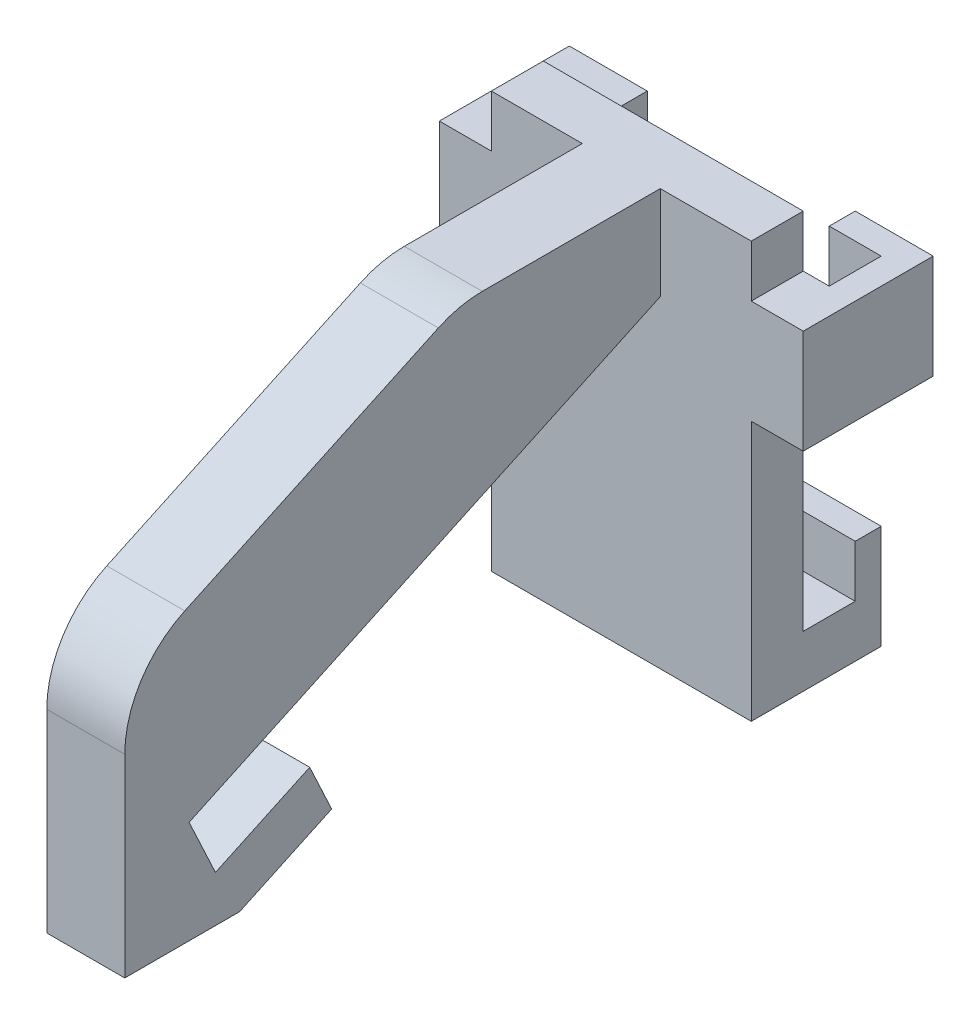
SolidWorks part; units mm, degrees
ref_plane "Front" through (0, 0, 0) normal (0, 0, 1) x (1, 0, 0)
ref_plane "Top" through (0, 0, 0) normal (0, 1, 0) x (1, 0, 0)
ref_plane "Right" through (0, 0, 0) normal (1, 0, 0) x (0, 0, -1)
sketch "Sketch2" plane through (0, 0, 0) normal (1, 0, 0) x (0, 0, -1)
  line L0 (0, 0) -> (25, 0)
  line L1 (25, 0) -> (25, 20)
  line L2 (25, 20) -> (20, 20)
  line L3 (20, 20) -> (20, 10)
  line L4 (20, 10) -> (10, 10)
  line L5 (10, 10) -> (10, 80)
  line L6 (10, 80) -> (0, 80)
  line L7 (0, 80) -> (0, 0)
  dimension "D1" = 25
  dimension "D2" = 10
  dimension "D3" = 5
  dimension "D4" = 80
  dimension "D5" = 70
  dimension "D6" = 20
extrude "Boss-Extrude2" add sketch "Sketch2" along normal blind 50
ref_plane "Plane1" through (0, 70, 0) normal (0, 1, 0) x (1, 0, 0)
sketch "Sketch3" plane through (0, 70, 0) normal (0, 1, 0) x (1, 0, 0)
  line L0 (50, 0) -> (60, 0)
  line L1 (60, 0) -> (60, 25)
  line L2 (60, 25) -> (45, 25)
  line L4 (45, 25) -> (45, 20)
  line L5 (50, 20) -> (0, 20) construction
  line L6 (45, 20) -> (50, 20)
  line L7 (50, 20) -> (55, 20)
  line L8 (55, 20) -> (55, 10)
  line L9 (55, 10) -> (50, 10)
  line L10 (50, 10) -> (50, 0)
  dimension "D1" = 25
  dimension "D2" = 5
  dimension "D3" = 10
  dimension "D4" = 15
extrude "Boss-Extrude3" add sketch "Sketch3" against normal blind 20
ref_plane "Plane2" through (25, 0, 0) normal (1, 0, 0) x (0, 0, -1)
mirror "Mirror1" about plane through (25, 0, 0) normal (1, 0, 0) of "Boss-Extrude3"
sketch "Sketch5" plane through (25, 0, 0) normal (1, 0, 0) x (0, 0, -1)
  line L0 (0, 80) -> (-38.6706, 80)
  line L7 (-103.0058, 50) -> (-103.0058, 0)
  line L12 (-90.6308, 19.7382) -> (-85.5594, 8.8625)
  line L16 (-85.5594, 8.8625) -> (-67.4332, 17.3148)
  line L17 (-67.4332, 17.3148) -> (-63.207, 8.2518)
  line L18 (-63.207, 8.2518) -> (-80.903, 0)
  line L21 (39.3065, 0) -> (-107.1086, 0) construction
  line L23 (0, 80) -> (0, 62)
  line L24 (0, 50) -> (0, 70) construction
  line L25 (0, 62) -> (-90.6308, 19.7382)
  line L26 (-80.903, 0) -> (-103.0058, 0)
  line L27 (-38.6706, 80) -> (-103.0058, 50)
  point P1 (0, 0)
  point P17 (0, 0)
  dimension "D1" = 18
  dimension "D2" = 25
  dimension "D3" = 90
  dimension "D4" = 100
  dimension "D5" = 10
  dimension "D6" = 50
  dimension "D7" = 20
  dimension "D8" = 12
  dimension "D9" = 103.0058
extrude "Boss-Extrude4" add sketch "Sketch5" along normal mid plane 15
fillet "Fillet2" radius 20 1 edges at (25, 80, 38.6706)
fillet "Fillet3" radius 20 1 edges at (25, 50, 103.0058)
